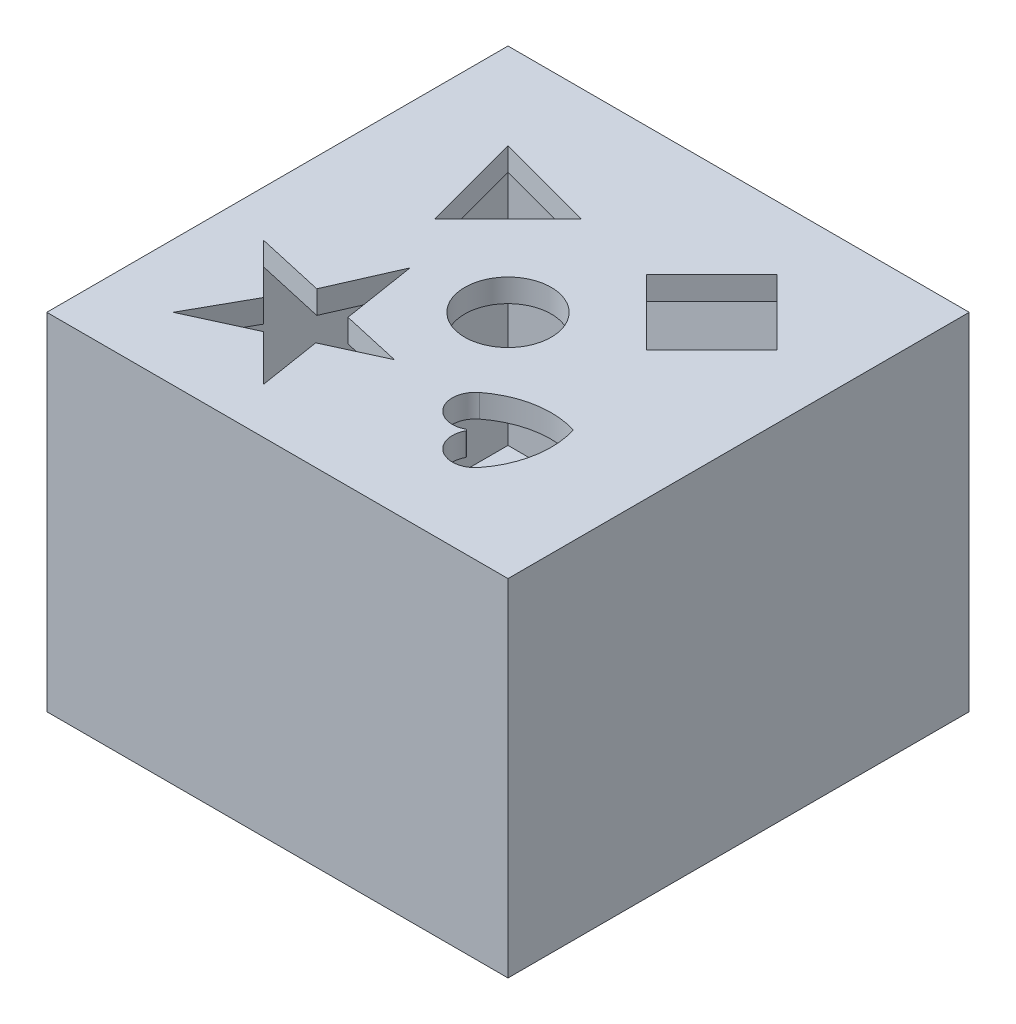
SolidWorks part; units mm, degrees
ref_plane "Front Plane" through (0, 0, 0) normal (0, 0, 1) x (1, 0, 0)
ref_plane "Top Plane" through (0, 0, 0) normal (0, 1, 0) x (1, 0, 0)
ref_plane "Right Plane" through (0, 0, 0) normal (1, 0, 0) x (0, 0, -1)
sketch "Sketch1" plane through (0, 0, 0) normal (0, 1, 0) x (1, 0, 0)
  line L1 (-20, 20) -> (20, 20)
  line L2 (-20, 20) -> (-20, -20)
  line L3 (-20, -20) -> (20, -20)
  line L4 (20, 20) -> (20, -20)
  line L5 (-20, 20) -> (20, -20) construction
  line L6 (-20, -20) -> (20, 20) construction
  point P0 (0, 0)
  dimension "D1" = 40
extrude "Boss-Extrude1" add sketch "Sketch1" along normal mid plane 30
ref_plane "Plane1" through (0, 13, 0) normal (0, 1, 0) x (1, 0, 0)
sketch "Sketch2" plane through (0, 13, 0) normal (0, 1, 0) x (1, 0, 0)
  line L1 (-18, 18) -> (18, 18)
  line L2 (-18, 18) -> (-18, -18)
  line L3 (-18, -18) -> (18, -18)
  line L4 (18, 18) -> (18, -18)
  line L5 (-18, 18) -> (18, -18) construction
  line L6 (-18, -18) -> (18, 18) construction
  point P0 (0, 0)
  dimension "D1" = 36
extrude "Cut-Extrude1" cut sketch "Sketch2" against normal blind 26
sketch "Sketch4" plane through (0, 15, 0) normal (0, 1, 0) x (1, 0, 0)
  line L0 (-15.9976, -5.1913) -> (-10.0569, -6.528)
  line L1 (-20, -20) -> (20, -20) construction
  line L2 (-20, -20) -> (-20, 20) construction
  line L3 (-20, 20) -> (20, 20) construction
  line L4 (20, -20) -> (20, 20) construction
  line L5 (-20, -20) -> (20, 20) construction
  line L6 (-20, 20) -> (20, -20) construction
  line L7 (-17.6777, 0) -> (0, -17.6777) construction
  line L8 (0, -17.6777) -> (17.6777, 0) construction
  line L9 (17.6777, 0) -> (0, 17.6777) construction
  line L10 (0, 17.6777) -> (-17.6777, 0) construction
  line L18 (14.4957, 8.8388) -> (8.8388, 14.4957)
  line L19 (8.8388, 14.4957) -> (3.182, 8.8388)
  line L20 (3.182, 8.8388) -> (8.8388, 3.182)
  line L21 (8.8388, 3.182) -> (14.4957, 8.8388)
  line L22 (-12.5131, 12.5131) -> (-10.1837, 3.8197)
  line L23 (-10.1837, 3.8197) -> (-3.8197, 10.1837)
  line L24 (-3.8197, 10.1837) -> (-12.5131, 12.5131)
  line L25 (-14.52, -14.52) -> (-5.1913, -15.9976) construction
  line L26 (-5.1913, -15.9976) -> (-0.9033, -7.582) construction
  line L27 (-0.9033, -7.582) -> (-7.582, -0.9033) construction
  line L28 (-7.582, -0.9033) -> (-15.9976, -5.1913) construction
  line L29 (-15.9976, -5.1913) -> (-14.52, -14.52) construction
  line L30 (-1.363, -8.4842) -> (-6.0414, -10.6304)
  line L31 (-14.52, -14.52) -> (-11.7067, -9.4822)
  line L32 (-7.582, -0.9033) -> (-6.5667, -7.3133)
  line L33 (-5.1913, -15.9976) -> (-9.1379, -12.051)
  line L34 (-6.5667, -7.3133) -> (-1.363, -8.4842)
  line L35 (-6.0414, -10.6304) -> (-5.1913, -15.9976)
  line L36 (-11.7067, -9.4822) -> (-15.9976, -5.1913)
  line L37 (-10.0569, -6.528) -> (-7.582, -0.9033)
  line L38 (-9.1379, -12.051) -> (-14.52, -14.52)
  line L72 (14.4957, -8.8388) -> (8.8388, -3.182) construction
  line L73 (8.8388, -3.182) -> (3.182, -8.8388) construction
  line L74 (3.182, -8.8388) -> (8.8388, -14.4957) construction
  line L75 (8.8388, -14.4957) -> (14.4957, -8.8388) construction
  line L76 (6.0104, -6.0104) -> (6.0104, -11.6673) construction
  line L77 (6.0104, -11.6673) -> (11.6673, -11.6673) construction
  line L78 (11.6673, -11.6673) -> (11.6673, -6.0104) construction
  line L79 (11.6673, -6.0104) -> (6.0104, -6.0104) construction
  circle A0 centre (0, 0) radius 3.75
  circle A1 centre (0, 0) radius 12.5 construction
  circle A2 centre (8.8388, 8.8388) radius 4 construction
  circle A3 centre (-8.8388, 8.8388) radius 2.5981 construction
  circle A4 centre (-8.8388, -8.8388) radius 6.5 construction
  circle A5 centre (8.8388, -8.8388) radius 4 construction
  circle A21 centre (8.8388, -8.8388) radius 2.8284 construction
  arc A32 (10.4111, -12.9034) -> (11.6673, -6.0104) centre (4.5151, -8.268) ccw
  arc A33 (4.7743, -7.2666) -> (11.6673, -6.0104) centre (9.4097, -13.1626) cw
  arc A34 (7.4246, -10.253) -> (10.4111, -12.9034) centre (8.8388, -11.6673) ccw
  arc A35 (4.7743, -7.2666) -> (7.4246, -10.253) centre (6.0104, -8.8388) ccw
  dimension "D1" = 7.5
  dimension "D5" = 13
  dimension "D2" = 25
  dimension "D3" = 8
  dimension "D4" = 9
  dimension "D6" = 8
extrude "Cut-Extrude4" cut sketch "Sketch4" against normal blind 2
fillet "Fillet1" radius 0.1 1 edges at (7.4246, 14, 10.253)
